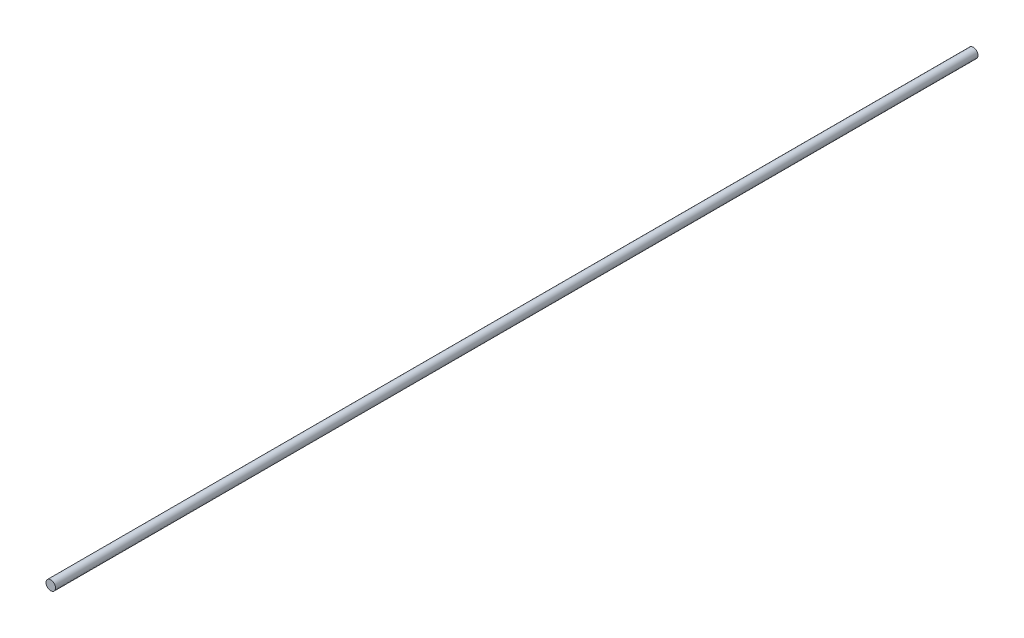
SolidWorks part; units mm, degrees
material "Alloy Steel"
ref_plane "Front Plane" through (0, 0, 0) normal (0, 0, 1) x (1, 0, 0)
ref_plane "Top Plane" through (0, 0, 0) normal (0, 1, 0) x (1, 0, 0)
ref_plane "Right Plane" through (0, 0, 0) normal (1, 0, 0) x (0, 0, -1)
sketch "Sketch1" plane through (0, 0, 0) normal (0, 0, 1) x (1, 0, 0)
  circle A0 centre (0, 0) radius 10
extrude "Boss-Extrude1" add sketch "Sketch1" along normal blind 1940
